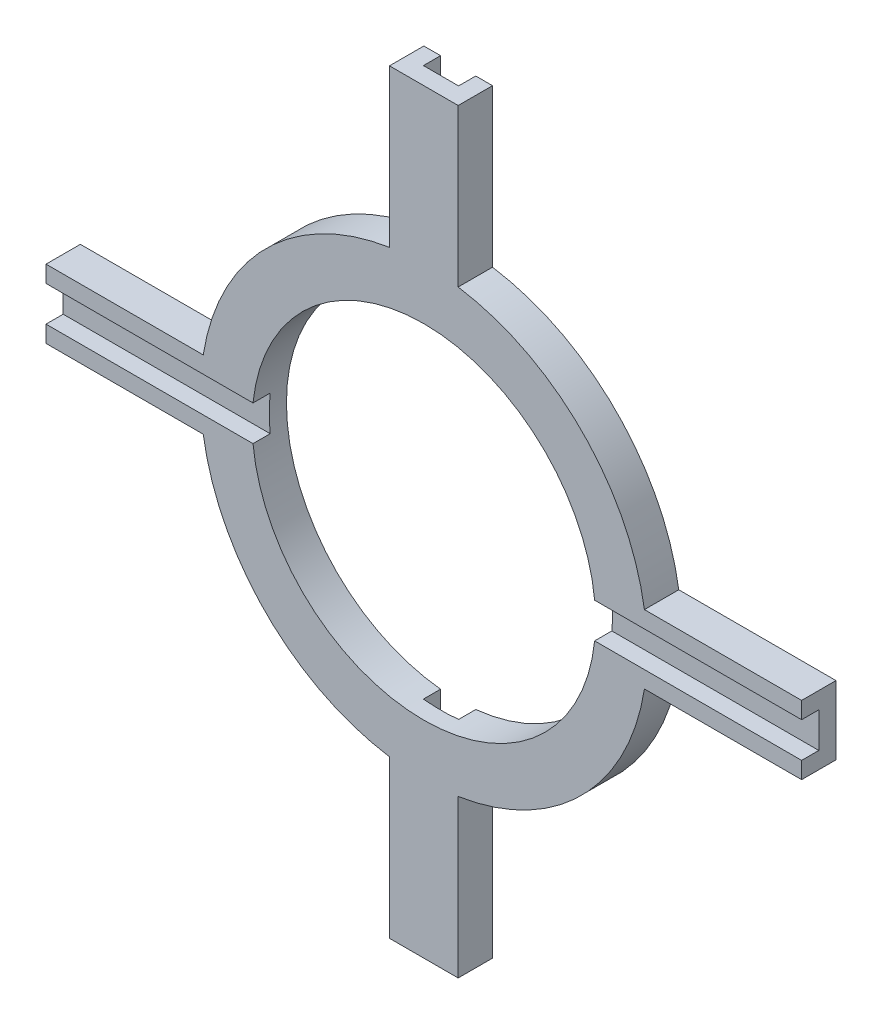
SolidWorks part; units mm, degrees
material "POM Acetal Copolymer"
ref_plane "Front Plane" through (0, 0, 0) normal (0, 0, 1) x (1, 0, 0)
ref_plane "Top Plane" through (0, 0, 0) normal (0, 1, 0) x (1, 0, 0)
ref_plane "Right Plane" through (0, 0, 0) normal (1, 0, 0) x (0, 0, -1)
sketch "Sketch1" plane through (0, 0, 0) normal (0, 0, 1) x (1, 0, 0)
  circle A0 centre (0, 0) radius 26
  circle A1 centre (0, 0) radius 20
extrude "Relieved_Floating_Ring" add sketch "Sketch1" along normal blind 4
sketch "Sketch2" plane through (0, 0, 0) normal (0, 0, 1) x (1, 0, 0)
  line L1 (-44, -4) -> (-24, -4)
  line L2 (-44, -4) -> (-44, 4)
  line L3 (-44, 4) -> (-24, 4)
  line L4 (-24, -4) -> (-24, 4)
extrude "X_Slide_Pad_-1" add sketch "Sketch2" along normal blind 4
sketch "Sketch3" plane through (0, 0, 0) normal (0, 0, 1) x (1, 0, 0)
  line L1 (-4, -44) -> (4, -44)
  line L2 (-4, -44) -> (-4, -24)
  line L3 (-4, -24) -> (4, -24)
  line L4 (4, -44) -> (4, -24)
extrude "Y_Slide_Pad_-1" add sketch "Sketch3" along normal blind 4
sketch "Sketch4" plane through (0, 0, 0) normal (0, 0, 1) x (1, 0, 0)
  line L1 (24, -4) -> (44, -4)
  line L2 (24, -4) -> (24, 4)
  line L3 (24, 4) -> (44, 4)
  line L4 (44, -4) -> (44, 4)
extrude "X_Slide_Pad_1" add sketch "Sketch4" along normal blind 4
sketch "Sketch5" plane through (0, 0, 0) normal (0, 0, 1) x (1, 0, 0)
  line L1 (-4, 24) -> (4, 24)
  line L2 (-4, 24) -> (-4, 44)
  line L3 (-4, 44) -> (4, 44)
  line L4 (4, 24) -> (4, 44)
extrude "Y_Slide_Pad_1" add sketch "Sketch5" along normal blind 4
sketch "Sketch6" plane through (0, 0, 0) normal (0, 0, -1) x (-1, 0, 0)
  line L0 (2.05, -45) -> (-2.05, -45)
  line L1 (-2.05, -45) -> (-2.05, 45)
  line L2 (-2.05, 45) -> (2.05, 45)
  line L3 (2.05, 45) -> (2.05, -45)
extrude "Lower_Y_Slots_W4p1_H2" cut sketch "Sketch6" against normal blind 2
sketch "Sketch7" plane through (0, 0, 4) normal (0, 0, 1) x (1, 0, 0)
  line L0 (-45, -2.05) -> (45, -2.05)
  line L1 (45, -2.05) -> (45, 2.05)
  line L2 (45, 2.05) -> (-45, 2.05)
  line L3 (-45, 2.05) -> (-45, -2.05)
extrude "Upper_X_Slots_W4p1_H2" cut sketch "Sketch7" against normal blind 2
